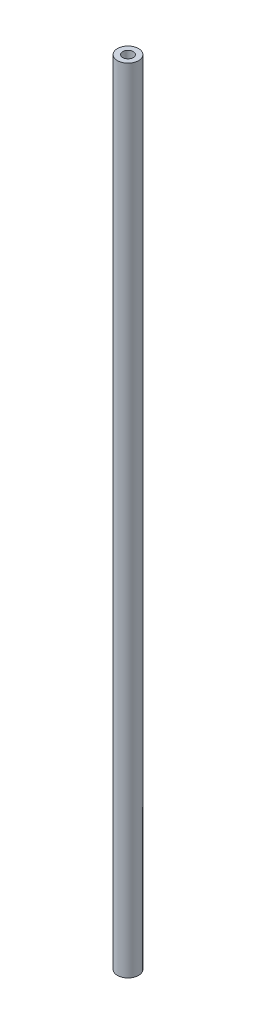
SolidWorks part; units mm, degrees
material "AISI 304"
ref_plane "Ön Düzlem" through (0, 0, 0) normal (0, 0, 1) x (1, 0, 0)
ref_plane "Üst Düzlem" through (0, 0, 0) normal (0, 1, 0) x (1, 0, 0)
ref_plane "Sağ Düzlem" through (0, 0, 0) normal (1, 0, 0) x (0, 0, -1)
sketch "Sketch1" plane through (0, 0, 0) normal (0, 1, 0) x (1, 0, 0)
  circle A0 centre (0, 0) radius 7
  dimension "D1" = 14
extrude "Boss-Extrude1" add sketch "Sketch1" along normal blind 527.5
sketch "Sketch2" plane through (0, 527.5, 0) normal (0, 1, 0) x (1, 0, 0)
  circle A0 centre (0, 0) radius 3.5
  dimension "D1" = 7
extrude "Cut-Extrude1" cut sketch "Sketch2" against normal through all
